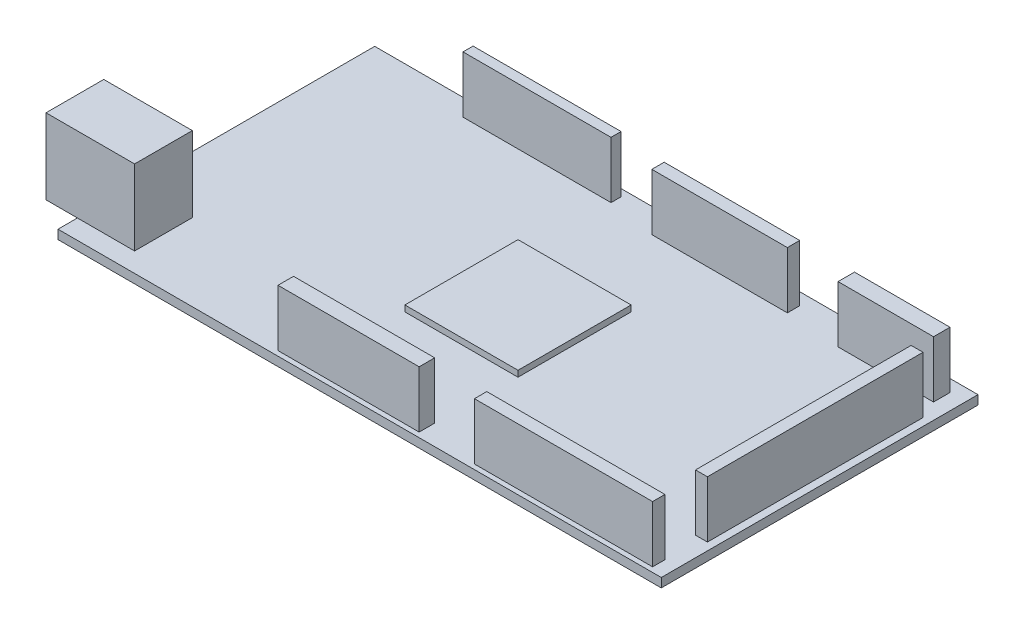
SolidWorks part; units mm, degrees
ref_plane "Front Plane" through (0, 0, 0) normal (0, 0, 1) x (1, 0, 0)
ref_plane "Top Plane" through (0, 0, 0) normal (0, 1, 0) x (1, 0, 0)
ref_plane "Right Plane" through (0, 0, 0) normal (1, 0, 0) x (0, 0, -1)
sketch "Sketch1" plane through (0, 0, 0) normal (0, 1, 0) x (1, 0, 0)
  line L1 (50.8, -26.67) -> (-50.8, -26.67)
  line L2 (50.8, -26.67) -> (50.8, 26.67)
  line L3 (50.8, 26.67) -> (-50.8, 26.67)
  line L4 (-50.8, -26.67) -> (-50.8, 26.67)
  line L5 (50.8, -26.67) -> (-50.8, 26.67) construction
  line L6 (50.8, 26.67) -> (-50.8, -26.67) construction
  point P0 (0, 0)
  dimension "D1" = 101.6
  dimension "D2" = 53.34
extrude "Boss-Extrude1" add sketch "Sketch1" along normal blind 1.524
sketch "Sketch2" plane through (0, 1.524, 0) normal (0, 1, 0) x (1, 0, 0)
  line L1 (-9.525, 9.525) -> (9.525, 9.525)
  line L2 (-9.525, 9.525) -> (-9.525, -9.525)
  line L3 (-9.525, -9.525) -> (9.525, -9.525)
  line L4 (9.525, 9.525) -> (9.525, -9.525)
  line L5 (-9.525, 9.525) -> (9.525, -9.525) construction
  line L6 (-9.525, -9.525) -> (9.525, 9.525) construction
  point P0 (0, 0)
  dimension "D1" = 19.05
extrude "Boss-Extrude2" add sketch "Sketch2" along normal blind 1.016
sketch "Sketch3" plane through (0, 1.524, 0) normal (0, 1, 0) x (1, 0, 0)
  line L1 (-56.0893, -13.675) -> (-41.1711, -13.675)
  line L2 (-56.0893, -13.675) -> (-56.0893, -23.401)
  line L3 (-56.0893, -23.401) -> (-41.1711, -23.401)
  line L4 (-41.1711, -13.675) -> (-41.1711, -23.401)
extrude "Boss-Extrude3" add sketch "Sketch3" along normal blind 12.7
sketch "Sketch4" plane through (0, 1.524, 0) normal (0, 1, 0) x (1, 0, 0)
  line L1 (-33.034, 25.4655) -> (-8.107, 25.4655)
  line L2 (-33.034, 25.4655) -> (-33.034, 23.773)
  line L3 (-33.034, 23.773) -> (-8.107, 23.773)
  line L4 (-8.107, 25.4655) -> (-8.107, 23.773)
  line L5 (0, 24.6193) -> (22.8209, 24.6193)
  line L6 (0, 24.6193) -> (0, 22.542)
  line L7 (0, 22.542) -> (22.8209, 22.542)
  line L8 (22.8209, 24.6193) -> (22.8209, 22.542)
  line L9 (32.0531, 24.6193) -> (48.1326, 24.6193)
  line L10 (32.0531, 24.6193) -> (32.0531, 21.8496)
  line L11 (32.0531, 21.8496) -> (48.1326, 21.8496)
  line L12 (48.1326, 24.6193) -> (48.1326, 21.8496)
  line L13 (49.5174, 18.6952) -> (47.5171, 18.6952)
  line L14 (49.5174, 18.6952) -> (49.5174, -17.6182)
  line L15 (49.5174, -17.6182) -> (47.5171, -17.6182)
  line L16 (47.5171, 18.6952) -> (47.5171, -17.6182)
  line L17 (18.5125, -23.773) -> (48.5173, -23.773)
  line L18 (18.5125, -23.773) -> (18.5125, -25.8502)
  line L19 (18.5125, -25.8502) -> (48.5173, -25.8502)
  line L20 (48.5173, -23.773) -> (48.5173, -25.8502)
  line L21 (-14.5696, -23.2344) -> (9.2034, -23.2344)
  line L22 (-14.5696, -23.2344) -> (-14.5696, -25.8502)
  line L23 (-14.5696, -25.8502) -> (9.2034, -25.8502)
  line L24 (9.2034, -23.2344) -> (9.2034, -25.8502)
extrude "Boss-Extrude4" add sketch "Sketch4" along normal blind 9.525
